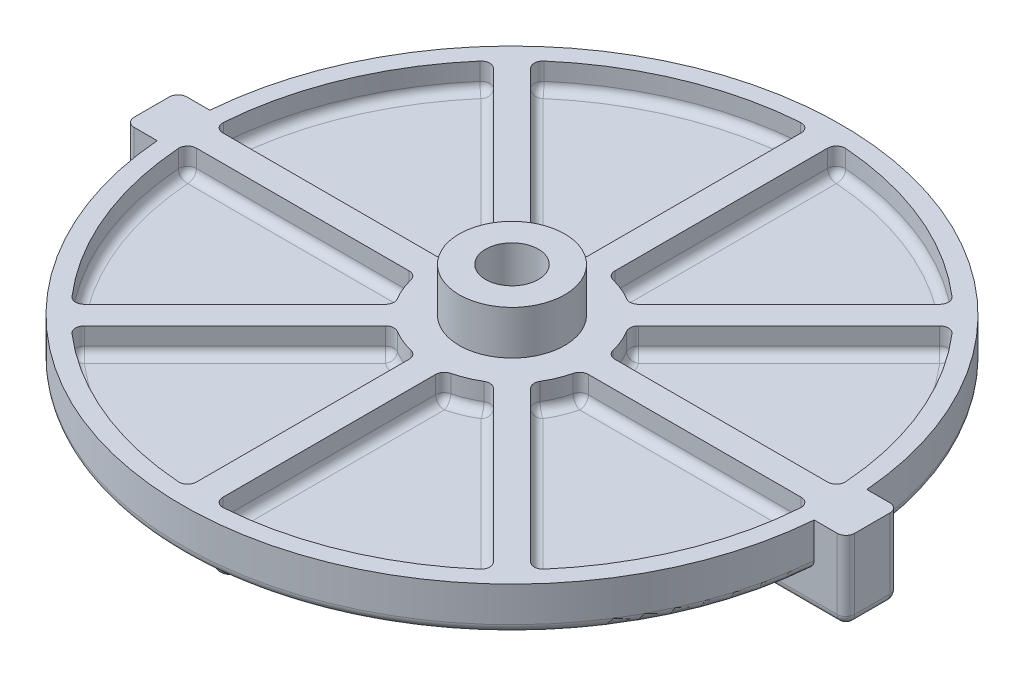
SolidWorks part; units mm, degrees
ref_plane "Front Plane" through (0, 0, 0) normal (0, 0, 1) x (1, 0, 0)
ref_plane "Top Plane" through (0, 0, 0) normal (0, 1, 0) x (1, 0, 0)
ref_plane "Right Plane" through (0, 0, 0) normal (1, 0, 0) x (0, 0, -1)
sketch "Sketch1" plane through (0, 0, 0) normal (0, 1, 0) x (1, 0, 0)
  circle A0 centre (0, 0) radius 37.5
  dimension "D1" = 75
extrude "Boss-Extrude1" add sketch "Sketch1" along normal blind 5
shell "Shell1" thickness 2
sketch "Sketch2" plane through (0, 2, 0) normal (0, 1, 0) x (1, 0, 0)
  circle A0 centre (0, 0) radius 9.5
  dimension "D1" = 19
extrude "Boss-Extrude2" add sketch "Sketch2" along normal up to surface (3 mm away) up to face at (0, 5, 35.5)
sketch "Sketch3" plane through (0, 5, 0) normal (0, 1, 0) x (1, 0, 0)
  circle A0 centre (0, 0) radius 6
  dimension "D1" = 12
extrude "Boss-Extrude3" add sketch "Sketch3" along normal blind 5
sketch "Sketch4" plane through (0, 5, 0) normal (0, 1, 0) x (1, 0, 0)
  line L0 (0, 0) -> (35.5, 0)
  circle A0 centre (0, 0) radius 35.5 construction
rib "Rib1" sketch "Sketch4" sketch "Sketch4" thickness 3 extrusion direction normal to sketch draft on no parameters "D1"=3
pattern_circular "CirPattern1" count 8 over 360 about axis through (0, 0, 0) along (0, 1, 0) of "Rib1"
sketch "Sketch5" plane through (0, 0, 0) normal (0, -1, 0) x (1, 0, 0)
  line L0 (0, -17) -> (0, -32) construction
  line L1 (1.5, -17) -> (1.5, -32)
  line L2 (-1.5, -17) -> (-1.5, -32)
  line L3 (1.5, -35.4683) -> (1.5, -9.3808) construction
  arc A0 (1.5, -17) -> (-1.5, -17) centre (0, -17) ccw
  arc A1 (-1.5, -32) -> (1.5, -32) centre (0, -32) ccw
  circle A2 centre (0, 0) radius 32 construction
  point P3 (0, -24.5)
  dimension "D2" = 64
  dimension "D1" = 15
extrude "Boss-Extrude4" add sketch "Sketch5" along normal blind 4
mirror "Mirror1" about plane through (0, 0, 0) normal (0, 0, 1) of "Boss-Extrude4"
sketch "Sketch6" plane through (0, 0, 0) normal (0, -1, 0) x (1, 0, 0)
  line L0 (0, 0) -> (37.5, 0) construction
  line L1 (0, 0) -> (0, 40.6224) construction
  line L2 (-41, 3) -> (41, 3)
  line L3 (-41, 3) -> (-41, -3)
  line L4 (-41, -3) -> (41, -3)
  line L5 (41, 3) -> (41, -3)
  circle A0 centre (0, 0) radius 37.5 construction
  dimension "D1" = 82
  dimension "D2" = 6
extrude "Boss-Extrude5" add sketch "Sketch6" along normal up to surface (4 mm away) up to face at (0, -4, 24.5)
sketch "Sketch7" plane through (0, 0, 0) normal (0, 1, 0) x (1, 0, 0)
  line L3 (41, 3) -> (37.3798, 3)
  line L4 (37.3798, -3) -> (41, -3)
  line L5 (41, -3) -> (41, 3)
  line L6 (41, 3) -> (37.3798, 3)
  line L7 (37.3798, -3) -> (41, -3)
  line L8 (41, -3) -> (41, 3)
  arc A1 (37.3798, -3) -> (37.3798, 3) centre (0, 0) ccw
  arc A2 (37.3798, -3) -> (37.3798, 3) centre (0, 0) ccw
  dimension "D1" = 0
extrude "Boss-Extrude6" add sketch "Sketch7" along normal up to surface (5 mm away) up to face at (8.3792, 5, -20.2291)
sketch "Sketch8" plane through (0, 0, 0) normal (0, 1, 0) x (1, 0, 0)
  line L3 (-41, -3) -> (-37.3798, -3)
  line L4 (-37.3798, 3) -> (-41, 3)
  line L5 (-41, 3) -> (-41, -3)
  line L6 (-41, -3) -> (-37.3798, -3)
  line L7 (-37.3798, 3) -> (-41, 3)
  line L8 (-41, 3) -> (-41, -3)
  arc A1 (-37.3798, 3) -> (-37.3798, -3) centre (0, 0) ccw
  arc A2 (-37.3798, 3) -> (-37.3798, -3) centre (0, 0) ccw
  dimension "D1" = 0
extrude "Boss-Extrude7" add sketch "Sketch8" along normal up to surface (5 mm away) up to face at (8.3792, 5, -20.2291)
hole_wizard "Ø6.0 (6) Diameter Hole1" positions "Sketch10" profile "Sketch9" hole size "Ø6.0" standard "ANSI Metric"
sketch "Sketch10" plane through (0, 10, 0) normal (0, 1, 0) x (1, 0, 0)
  point P0 (0, 0)
sketch "Sketch9" plane through (0, 10, 0) normal (1, 0, 0) x (0, 0, 1)
  line L0 (0, 0) -> (0, 9.8026)
  line L1 (0, 9.8026) -> (3, 8)
  line L2 (3, 8) -> (3, 0)
  line L5 (3, 0) -> (0, 0)
  line L10 (0, 9.8026) -> (-3, 8) construction
  line L11 (0, -6.35) -> (0, 107.95) construction
  dimension "Hole Dia." = 6
  dimension "Hole Depth" = 8
  dimension "Drill Angle" = 118
fillet "Fillet3" radius 1 32 edges at (-26.1405, 3.5, -24.0192) (-35.4683, 3.5, -1.5) (-9.3808, 3.5, -1.5) (-7.6939, 3.5, -5.5726) (-1.5, 3.5, -35.4683) (-24.0192, 3.5, -26.1405) (-5.5726, 3.5, -7.6939) (-1.5, 3.5, -9.3808) (35.4683, 3.5, 1.5) (9.3808, 3.5, 1.5) (7.6939, 3.5, 5.5726) (26.1405, 3.5, 24.0192) (24.0192, 3.5, 26.1405) (5.5726, 3.5, 7.6939) (1.5, 3.5, 9.3808) (1.5, 3.5, 35.4683) (-1.5, 3.5, 35.4683) (-1.5, 3.5, 9.3808) (-5.5726, 3.5, 7.6939) (-24.0192, 3.5, 26.1405) (35.4683, 3.5, -1.5) (26.1405, 3.5, -24.0192) (7.6939, 3.5, -5.5726) (-7.6939, 3.5, 5.5726) (-9.3808, 3.5, 1.5) (-35.4683, 3.5, 1.5) (-26.1405, 3.5, 24.0192) (24.0192, 3.5, -26.1405) (1.5, 3.5, -35.4683) (1.5, 3.5, -9.3808) (5.5726, 3.5, -7.6939) (9.3808, 3.5, -1.5)
fillet "Fillet4" radius 1 64 edges at (26.1351, 2, -23.5626) (32.7977, 2, -13.5853) (35.1416, 2, -1.819) (22.3037, 2, -1.5) (9.5808, 2, -1.7132) (8.7769, 2, -3.6355) (7.9861, 2, -5.5632) (1.819, 2, -35.1416) (13.5853, 2, -32.7977) (23.5626, 2, -26.1351) (5.5632, 2, -7.9861) (3.6355, 2, -8.7769) (1.7132, 2, -9.5808) (-23.5626, 2, -26.1351) (-13.5853, 2, -32.7977) (-1.819, 2, -35.1416) (-1.7132, 2, -9.5808) (-3.6355, 2, -8.7769) (-5.5632, 2, -7.9861) (-35.1416, 2, -1.819) (-32.7977, 2, -13.5853) (-26.1351, 2, -23.5626) (-7.9861, 2, -5.5632) (-8.7769, 2, -3.6355) (-9.5808, 2, -1.7132) (-26.1351, 2, 23.5626) (-32.7977, 2, 13.5853) (-35.1416, 2, 1.819) (-9.5808, 2, 1.7132) (-8.7769, 2, 3.6355) (-7.9861, 2, 5.5632) (-1.819, 2, 35.1416) (-13.5853, 2, 32.7977) (-23.5626, 2, 26.1351) (-5.5632, 2, 7.9861) (-3.6355, 2, 8.7769) (-1.7132, 2, 9.5808) (23.5626, 2, 26.1351) (13.5853, 2, 32.7977) (1.819, 2, 35.1416) (1.7132, 2, 9.5808) (3.6355, 2, 8.7769) (5.5632, 2, 7.9861) (26.1351, 2, 23.5626) (32.7977, 2, 13.5853) (35.1416, 2, 1.819) (22.3037, 2, 1.5) (9.5808, 2, 1.7132) (8.7769, 2, 3.6355) (7.9861, 2, 5.5632) (16.8317, 2, -14.7104) (14.7104, 2, -16.8317) (1.5, 2, -22.3037) (-1.5, 2, -22.3037) (-14.7104, 2, -16.8317) (-16.8317, 2, -14.7104) (-22.3037, 2, -1.5) (-22.3037, 2, 1.5) (-16.8317, 2, 14.7104) (-14.7104, 2, 16.8317) (-1.5, 2, 22.3037) (1.5, 2, 22.3037) (14.7104, 2, 16.8317) (16.8317, 2, 14.7104)
fillet "Fillet5" radius 1 2 edges at (41, -4, 0) (-41, -4, 0)
fillet "Fillet6" radius 1 28 edges at (-41, 1, -3) (-40.7071, -3.7071, -3) (41, 1, -3) (40.7071, -3.7071, -3) (41, 1, 3) (40.7071, -3.7071, 3) (-41, 1, 3) (-40.7071, -3.7071, 3) (0, -4, -33.5) (1.5, -4, -24.5) (0, -4, -15.5) (-1.5, -4, -24.5) (0, 0, -15.5) (1.5, 0, -24.5) (0, 0, -33.5) (-1.5, 0, -24.5) (0, -4, 15.5) (1.5, -4, 24.5) (0, -4, 33.5) (-1.5, -4, 24.5) (0, 0, 33.5) (1.5, 0, 24.5) (0, 0, 15.5) (-1.5, 0, 24.5) (0, -4, -3) (0, -4, 3) (0, 0, -37.5) (0, 0, 37.5)
